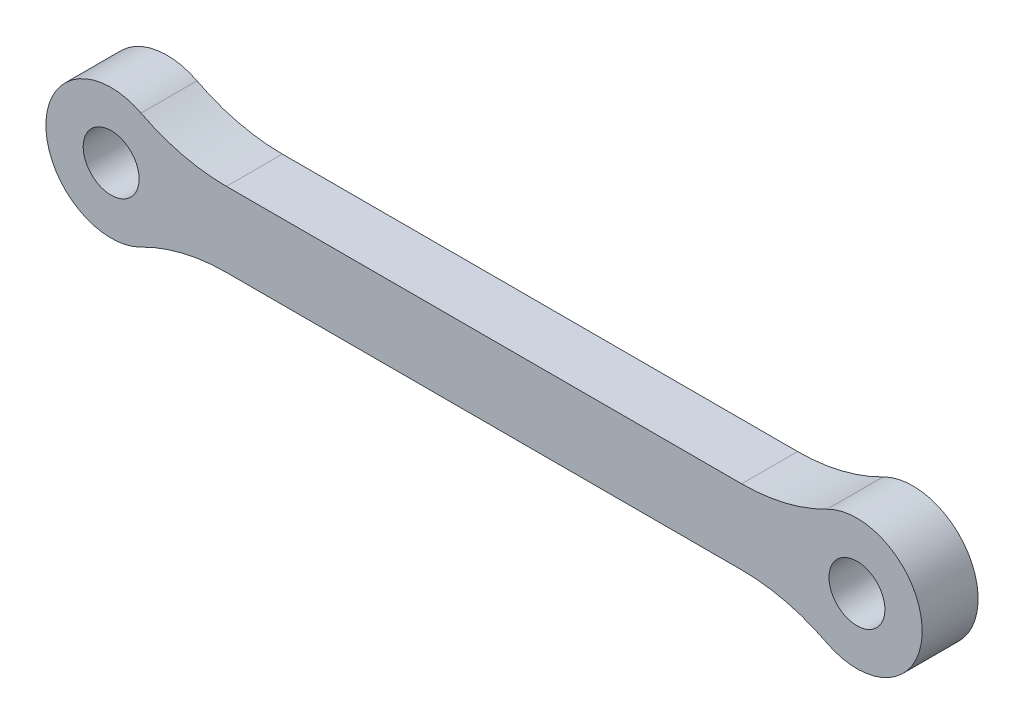
SolidWorks part; units mm, degrees
ref_plane "Front Plane" through (0, 0, 0) normal (0, 0, 1) x (1, 0, 0)
ref_plane "Top Plane" through (0, 0, 0) normal (0, 1, 0) x (1, 0, 0)
ref_plane "Right Plane" through (0, 0, 0) normal (1, 0, 0) x (0, 0, -1)
sketch "Sketch1" plane through (0, 0, 0) normal (0, 0, 1) x (1, 0, 0)
  line L0 (-20, 9.0017) -> (-20, -4.7068) construction
  line L1 (-33.8153, 2) -> (-6.1847, 2)
  line L2 (-37.36, 0) -> (-3.5, 0) construction
  line L3 (-33.8153, -2) -> (-6.1847, -2)
  arc A0 (-1.6034, -3.1111) -> (-1.6034, 3.1111) centre (0, 0) ccw
  circle A1 centre (0, 0) radius 1.5
  circle A2 centre (-40, 0) radius 1.5
  arc A3 (-38.3966, -3.1111) -> (-38.3966, 3.1111) centre (-40, 0) cw
  arc A4 (-6.1847, 2) -> (-1.6034, 3.1111) centre (-6.1847, 12) ccw
  arc A5 (-6.1847, -2) -> (-1.6034, -3.1111) centre (-6.1847, -12) cw
  arc A6 (-33.8153, -2) -> (-38.3966, -3.1111) centre (-33.8153, -12) ccw
  arc A7 (-33.8153, 2) -> (-38.3966, 3.1111) centre (-33.8153, 12) cw
  point P15 (-2.8723, 2)
  point P18 (-2.8723, -2)
  point P21 (-37.1277, -2)
  point P24 (-37.1277, 2)
  dimension "D1" = 3
  dimension "D2" = 7
  dimension "D5" = 10
  dimension "D3" = 20
  dimension "D4" = 2
extrude "Boss-Extrude1" add sketch "Sketch1" along normal blind 3
